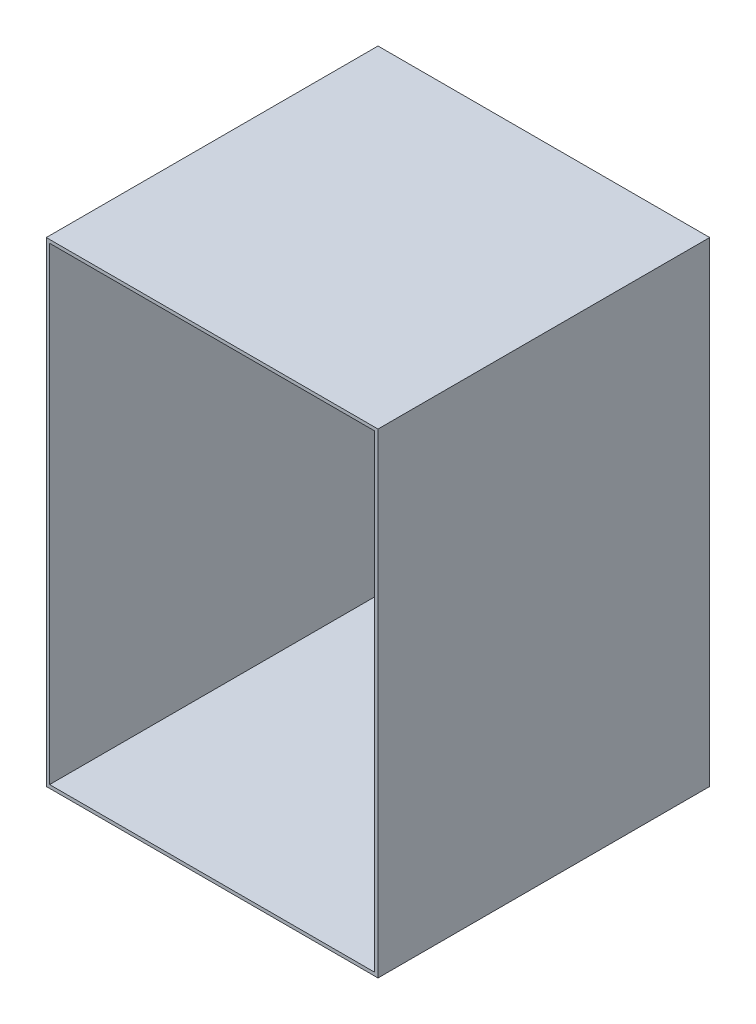
SolidWorks part; units mm, degrees
ref_plane "Plan de face" through (0, 0, 0) normal (0, 0, 1) x (1, 0, 0)
ref_plane "Plan de dessus" through (0, 0, 0) normal (0, 1, 0) x (1, 0, 0)
ref_plane "Plan de droite" through (0, 0, 0) normal (1, 0, 0) x (0, 0, -1)
sketch "Esquisse1" plane through (0, 0, 0) normal (0, 0, 1) x (1, 0, 0)
  line L1 (0, 0) -> (300, 0)
  line L2 (0, 0) -> (0, 430)
  line L3 (0, 430) -> (300, 430)
  line L4 (300, 0) -> (300, 430)
  dimension "D1" = 430
  dimension "D2" = 300
extrude "Boss.-Extru.1" add sketch "Esquisse1" against normal blind 300
sketch "Esquisse2" plane through (0, 0, 0) normal (0, 0, 1) x (1, 0, 0)
  line L14 (3, 3) -> (297, 3)
  line L15 (297, 3) -> (297, 427)
  line L16 (297, 427) -> (3, 427)
  line L17 (3, 427) -> (3, 3)
  line L18 (3, 3) -> (297, 3)
  line L19 (297, 3) -> (297, 427)
  line L20 (297, 427) -> (3, 427)
  line L21 (3, 427) -> (3, 3)
  dimension "D1" = 3
extrude "Enlèv. mat.-Extru.1" cut sketch "Esquisse2" against normal blind 297
